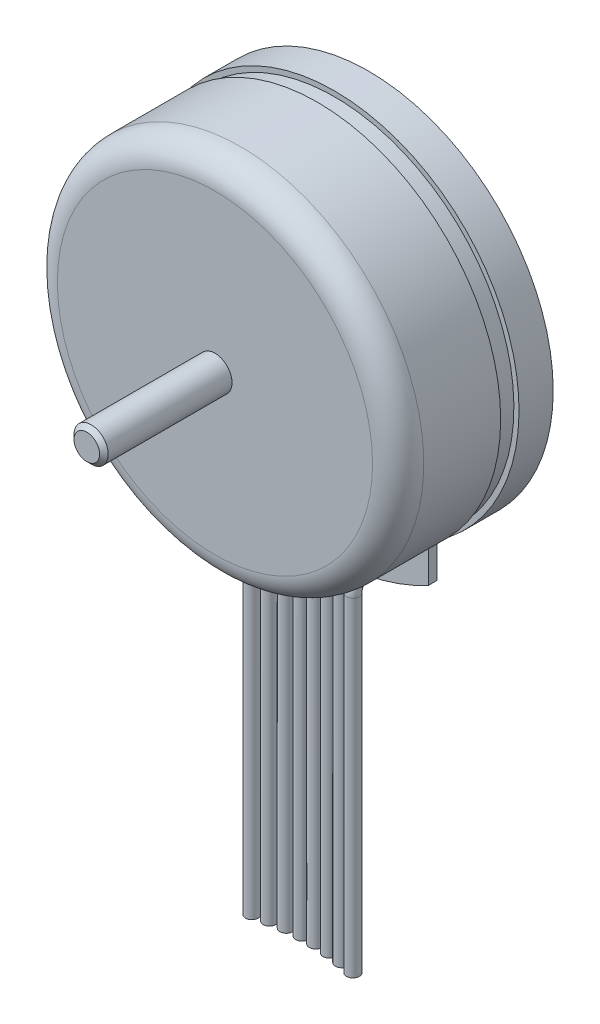
SolidWorks part; units mm, degrees
ref_plane "前视基准面" through (0, 0, 0) normal (0, 0, 1) x (1, 0, 0)
ref_plane "上视基准面" through (0, 0, 0) normal (0, 1, 0) x (1, 0, 0)
ref_plane "右视基准面" through (0, 0, 0) normal (1, 0, 0) x (0, 0, -1)
sketch "草图1" plane through (0, 0, 0) normal (0, 0, 1) x (1, 0, 0)
  circle A0 centre (0, 0) radius 21.6
  dimension "D1" = 43.2
extrude "拉伸1" add sketch "草图1" along normal blind 4
sketch "草图6" plane through (0, 0, 0) normal (0, 0, -1) x (-1, 0, 0)
  circle A0 centre (0, 0) radius 21.45
  dimension "D1" = 42.9
extrude "拉伸6" add sketch "草图6" against normal blind 18
sketch "草图2" plane through (0, 0, 18) normal (0, 0, 1) x (1, 0, 0)
  circle A0 centre (0, 0) radius 2
  dimension "D1" = 4
extrude "拉伸2" add sketch "草图2" along normal blind 15
sketch "草图3" plane through (0, 0, 0) normal (0, 0, -1) x (-1, 0, 0)
  line L0 (0, 0) -> (0, 11) construction
  circle A0 centre (0, 0) radius 11 construction
  circle A1 centre (0, 11) radius 1.25
  dimension "D1" = 22
  dimension "D2" = 2.5
extrude "拉伸3" cut sketch "草图3" against normal blind 3.9
cosmetic thread "装饰螺纹线1" parameters "D2"=3
pattern_circular "阵列(圆周)1" count 3 every 120 about axis through (0, 0, 0) along (0, 0, 1) of "拉伸3"
sketch "草图4" plane through (0, 0, 0) normal (0, 0, -1) x (-1, 0, 0)
  circle A0 centre (0, 0) radius 8
  dimension "D1" = 16
extrude "拉伸4" add sketch "草图4" along normal blind 3.2
sketch "草图5" plane through (0, 0, -3.2) normal (0, 0, -1) x (-1, 0, 0)
  circle A0 centre (0, 0) radius 2
  dimension "D1" = 4
extrude "拉伸5" add sketch "草图5" along normal blind 7.8
sketch "草图7" plane through (0, 0, 4) normal (0, 0, 1) x (1, 0, 0)
  circle A0 centre (0, 0) radius 21
  circle A1 centre (0, 0) radius 21.45
  circle A2 centre (0, 0) radius 21.45
  dimension "D2" = 42
  dimension "D1" = 0
extrude "拉伸7" cut sketch "草图7" along normal blind 2
sketch "草图9" plane through (0, 0, 4) normal (0, 0, 1) x (1, 0, 0)
  line L0 (0, 0) -> (0, -17.2337) construction
  line L1 (-12, -17.2337) -> (12, -17.2337)
  line L2 (-12, -17.2337) -> (-12, -38.5025)
  line L3 (-10, -40.5025) -> (14, -40.5025)
  line L4 (12, -17.2337) -> (12, -38.5025)
  line L5 (12, -38.5025) -> (14, -40.5025)
  line L6 (-12, -38.5025) -> (-10, -40.5025)
  circle A0 centre (0, 0) radius 21 construction
  point P1 (12, -40.5025)
  point P2 (-12, -40.5025)
  dimension "D1" = 24
extrude "拉伸9" add sketch "草图9" along normal blind 1
chamfer "倒角1" distance 0.5 angle 45 2 edges at (-2, 0, -11) (2, 0, 33)
fillet "圆角1" radius 3 1 edges at (-21.45, 0, 18)
sketch "草图10" plane through (0, 0, 0) normal (0, 0, -1) x (-1, 0, 0)
  line L0 (0, -21.6) -> (0, -25.1) construction
  circle A0 centre (0, 0) radius 25.1
  arc A1 (-12, -17.96) -> (12, -17.96) centre (0, 0) ccw construction
  dimension "D1" = 3.5
extrude "切除-拉伸1" cut sketch "草图10" against normal blind 10 flip side to cut
sketch "草图11" plane through (0, 0, 5) normal (0, 0, 1) x (1, 0, 0)
  line L0 (0, 0) -> (-0.8027, -22.986) construction
  line L1 (0, 0) -> (0, -23) construction
  circle A1 centre (-0.8027, -22.986) radius 0.75
  circle A2 centre (0, 0) radius 23 construction
  circle A3 centre (-2.5223, -22.8613) radius 0.75
  circle A4 centre (-4.2278, -22.6081) radius 0.75
  circle A5 centre (-5.9096, -22.2278) radius 0.75
  circle A6 centre (5.9096, -22.2278) radius 0.75
  circle A7 centre (4.2278, -22.6081) radius 0.75
  circle A8 centre (2.5223, -22.8613) radius 0.75
  circle A9 centre (0.8027, -22.986) radius 0.75
  point P15 (0, 0)
  dimension "D1" = 1.5
  dimension "D2" = 46
  dimension "D4" = 2
  dimension "D3" = 4
sketch "草图12" plane through (0, 0, 0) normal (1, 0, 0) x (0, 0, -1)
  line L0 (-5, -22.986) -> (-5.5, -22.986)
  line L1 (-5, -22.236) -> (-5, -23.736) construction
  line L2 (-7, -24.486) -> (-7, -62.986)
  arc A0 (-5.5, -22.986) -> (-7, -24.486) centre (-5.5, -24.486) ccw
  point P7 (-7, -22.986)
  dimension "D3" = 1.5
  dimension "D1" = 40
  dimension "D2" = 2
sweep "扫描1" add profiles "草图11" path "草图12"
